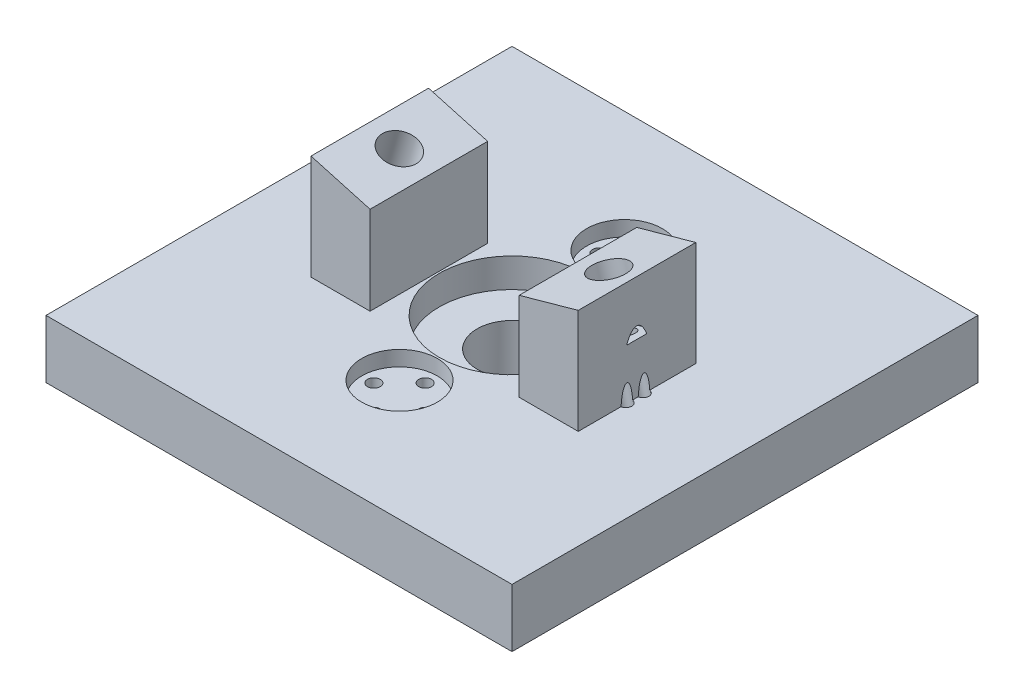
SolidWorks part; units mm, degrees
ref_plane "Front Plane" through (0, 0, 0) normal (0, 0, 1) x (1, 0, 0)
ref_plane "Top Plane" through (0, 0, 0) normal (0, 1, 0) x (1, 0, 0)
ref_plane "Right Plane" through (0, 0, 0) normal (1, 0, 0) x (0, 0, -1)
sketch "Sketch28" plane through (0, 0, 0) normal (0, 1, 0) x (1, 0, 0)
  line L1 (-38.0554, -35.7587) -> (41.9446, -35.7587)
  line L2 (-38.0554, -35.7587) -> (-38.0554, 44.2413)
  line L3 (-38.0554, 44.2413) -> (41.9446, 44.2413)
  line L4 (41.9446, -35.7587) -> (41.9446, 44.2413)
  dimension "D1" = 80
extrude "Boss-Extrude1" add sketch "Sketch28" along normal blind 10
hole_wizard "CBORE for M10 Cheese Head Screw1" positions "Sketch30" profile "Sketch29" counterbore size "M10" standard "AS" end condition through all
sketch "Sketch30" plane through (0, 10, 0) normal (0, 1, 0) x (1, 0, 0)
  point P0 (1.9446, 4.2413)
sketch "Sketch29" plane through (1.9446, 10, -4.2413) normal (1, 0, 0) x (0, 0, 1)
  line L0 (0, 0) -> (0, 10)
  line L1 (0, 10) -> (6, 10)
  line L3 (6, 10) -> (6, 5)
  line L4 (6, 5) -> (12.5, 5)
  line L5 (12.5, 5) -> (12.5, 0)
  line L7 (12.5, 0) -> (0, 0)
  line L11 (0, -6.35) -> (0, 107.95) construction
  dimension "Thru Hole Dia." = 12
  dimension "Thru Hole Depth" = 10
  dimension "C'Bore Dia." = 25
  dimension "C'Bore Depth" = 5
sketch "Sketch31" plane through (0, 0, 0) normal (0, -1, 0) x (-1, 0, 0)
  line L0 (-1.9446, 4.2413) -> (-12.4446, 4.2413) construction
  line L1 (-12.4446, 4.2413) -> (-14.4446, 4.2413) construction
  line L2 (-14.4446, 4.2413) -> (-14.4446, 16.7413) construction
  line L3 (-14.4446, 16.7413) -> (-14.4446, 18.7413) construction
  line L4 (-14.4446, 18.7413) -> (-12.4446, 18.7413) construction
  line L5 (-12.4446, 18.7413) -> (8.5554, 18.7413) construction
  line L6 (8.5554, 18.7413) -> (10.5554, 18.7413) construction
  line L7 (10.5554, 18.7413) -> (-1.9446, 18.7413) construction
  line L8 (-1.9446, 18.7413) -> (-1.9446, 4.2413) construction
  line L9 (10.5554, 18.7413) -> (10.5554, -5.2587) construction
  line L10 (10.5554, -5.2587) -> (-14.4446, -5.2587) construction
  line L11 (-14.4446, -5.2587) -> (-14.4446, 4.2413) construction
  line L13 (-14.4446, -5.2587) -> (10.5554, -5.2587)
  line L14 (-14.4446, -5.2587) -> (-14.4446, 18.7413)
  line L15 (-14.4446, 18.7413) -> (10.5554, 18.7413)
  line L16 (10.5554, -5.2587) -> (10.5554, 18.7413)
  circle A1 centre (-1.9446, 4.2413) radius 6
extrude "Boss-Extrude2" add sketch "Sketch31" along normal blind 5
sketch "Sketch36" plane through (0, -5, 0) normal (0, -1, 0) x (1, 0, 0)
  line L0 (14.4446, -18.7413) -> (12.4446, -18.7413) construction
  line L1 (-10.5554, -18.7413) -> (14.4446, -18.7413) construction
  line L2 (12.4446, -18.7413) -> (12.4446, -16.7413) construction
  line L3 (12.4446, -16.7413) -> (12.4446, -4.2413) construction
  line L4 (1.9446, -4.2413) -> (1.9446, -18.7413) construction
  circle A0 centre (12.4446, -16.7413) radius 1
  circle A1 centre (12.4446, -4.2413) radius 1
  circle A2 centre (-8.5554, -16.7413) radius 1
  circle A3 centre (-8.5554, -4.2413) radius 1
extrude "Boss-Extrude5" add sketch "Sketch36" along normal blind 5
sketch "Sketch37" plane through (0, 10, 0) normal (0, 1, 0) x (1, 0, 0)
  line L0 (-10.5554, 4.2413) -> (-38.0554, 4.2413) construction
  line L1 (-38.0554, 44.2413) -> (-38.0554, -35.7587) construction
  line L2 (-38.0554, 4.2413) -> (41.9446, 4.2413) construction
  line L3 (41.9446, -35.7587) -> (41.9446, 44.2413) construction
  circle A0 centre (1.9446, -15.0678) radius 6.5
  circle A1 centre (1.9446, 4.2413) radius 12.5 construction
  circle A2 centre (1.9446, 23.5504) radius 6.5
extrude "Cut-Extrude1" cut sketch "Sketch37" against normal blind 2.6
sketch "Sketch38" plane through (0, 7.4, 0) normal (0, 1, 0) x (1, 0, 0)
  line L0 (-4.5554, -15.0678) -> (1.9446, -15.0678) construction
  line L1 (1.9446, -15.0678) -> (8.4446, -15.0678) construction
  line L2 (8.4446, -15.0678) -> (1.9446, -15.0678) construction
  line L3 (1.9446, -15.0678) -> (1.9446, -21.5678) construction
  line L4 (1.9446, -21.5678) -> (1.9446, -8.5678) construction
  line L5 (1.9446, -21.5678) -> (1.9446, -19.4678) construction
  line L6 (-4.5554, -15.0678) -> (-2.4554, -15.0678) construction
  line L7 (1.9446, -8.5678) -> (1.9446, -10.6678) construction
  line L8 (8.4446, -15.0678) -> (6.3446, -15.0678) construction
  line L9 (1.9446, -8.5678) -> (1.9446, 4.2413) construction
  line L10 (1.9446, 4.2413) -> (-20.9557, 4.2413) construction
  circle A1 centre (1.9446, -15.0678) radius 6.5 construction
  circle A2 centre (1.9446, -19.4678) radius 1.1
  circle A3 centre (-2.4554, -15.0678) radius 1.1
  circle A4 centre (1.9446, -10.6678) radius 1.1
  circle A5 centre (6.3446, -15.0678) radius 1.1
  circle A6 centre (1.9446, 27.9504) radius 1.1
  circle A7 centre (6.3446, 23.5504) radius 1.1
  circle A8 centre (1.9446, 19.1504) radius 1.1
  circle A9 centre (-2.4554, 23.5504) radius 1.1
extrude "Cut-Extrude2" cut sketch "Sketch38" against normal through all
sketch "Sketch39" plane through (-3.1011, 10, 0) normal (0, 1, 0) x (1, 0, 0)
  line L1 (27.9855, 12.8593) -> (17.8455, 12.8593)
  line L2 (27.9855, 12.8593) -> (27.9855, -7.326)
  line L3 (27.9855, -7.326) -> (17.8455, -7.326)
  line L4 (17.8455, 12.8593) -> (17.8455, -7.326)
  line L5 (5.0456, -8.2587) -> (5.0456, -0.6085) construction
  line L6 (-7.7542, 12.8593) -> (-7.7542, -7.326)
  line L7 (-17.8942, -7.326) -> (-7.7542, -7.326)
  line L8 (-17.8942, 12.8593) -> (-17.8942, -7.326)
  line L9 (-17.8942, 12.8593) -> (-7.7542, 12.8593)
  circle A0 centre (5.0456, 4.2413) radius 12.5 construction
extrude "Boss-Extrude6" add sketch "Sketch39" along normal blind 18
sketch "Sketch41" plane through (-3.1011, 0, -12.8593) normal (0, 0, -1) x (-1, 0, 0)
  line L0 (-27.9855, 28) -> (-17.8455, 25.1661)
  line L2 (7.7542, 25.1661) -> (17.8942, 28)
  line L3 (7.7542, 28) -> (7.7542, 10) construction
  line L4 (7.7542, 28) -> (17.8942, 28) construction
  line L5 (-17.8455, 25.1661) -> (-17.8455, 28)
  line L6 (-17.8455, 28) -> (-27.9855, 28)
  line L7 (-27.9855, 28) -> (-17.8455, 25.1661)
  line L8 (17.8942, 28) -> (7.7542, 28)
  line L9 (7.7542, 28) -> (7.7542, 25.1661)
  line M3 (-17.8455, 10) -> (-17.8455, 28)
  line M4 (-17.8455, 28) -> (-27.9855, 28)
extrude "Cut-Extrude3" cut sketch "Sketch41" against normal up to next contours L0 M4 M3
sketch "Sketch42" plane through (-8.3319, 18.7169, 0) normal (-0.2692, 0.9631, 0) x (0.9631, 0.2692, 0)
  circle A0 centre (29.5194, 2.6975) radius 3
extrude "Cut-Extrude4" cut sketch "Sketch42" against normal blind 9
sketch "Sketch43" plane through (-3.0331, 10.8529, 0) normal (-0.2692, 0.9631, 0) x (0.9631, 0.2692, 0)
  circle A0 centre (26.4681, 1.0098) radius 1.0113
  circle A1 centre (26.4681, 3.9543) radius 1.0113
extrude "Cut-Extrude5" cut sketch "Sketch43" against normal through all
sketch "Sketch46" plane through (0, 0, -12.8593) normal (0, 0, -1) x (-1, 0, 0)
  line L0 (10.8552, 25.1661) -> (20.9952, 28)
  line L1 (10.8552, 28) -> (10.8552, 10) construction
  line L2 (20.9952, 28) -> (10.8552, 28)
  line L3 (10.8552, 28) -> (10.8552, 25.1661)
extrude "Cut-Extrude7" cut sketch "Sketch46" against normal up to next
sketch "Sketch47" plane through (5.7373, 20.529, 0) normal (0.2692, 0.9631, 0) x (0.9631, -0.2692, 0)
  circle A0 centre (-22.4926, 2.7667) radius 3
extrude "Cut-Extrude8" cut sketch "Sketch47" against normal blind 9
sketch "Sketch48" plane through (3.3149, 11.8611, 0) normal (0.2692, 0.9631, 0) x (0.9631, -0.2692, 0)
  circle A0 centre (-22.7181, 4.0756) radius 1
  circle A1 centre (-22.7181, 1.3839) radius 1
extrude "Cut-Extrude9" cut sketch "Sketch48" against normal through all
